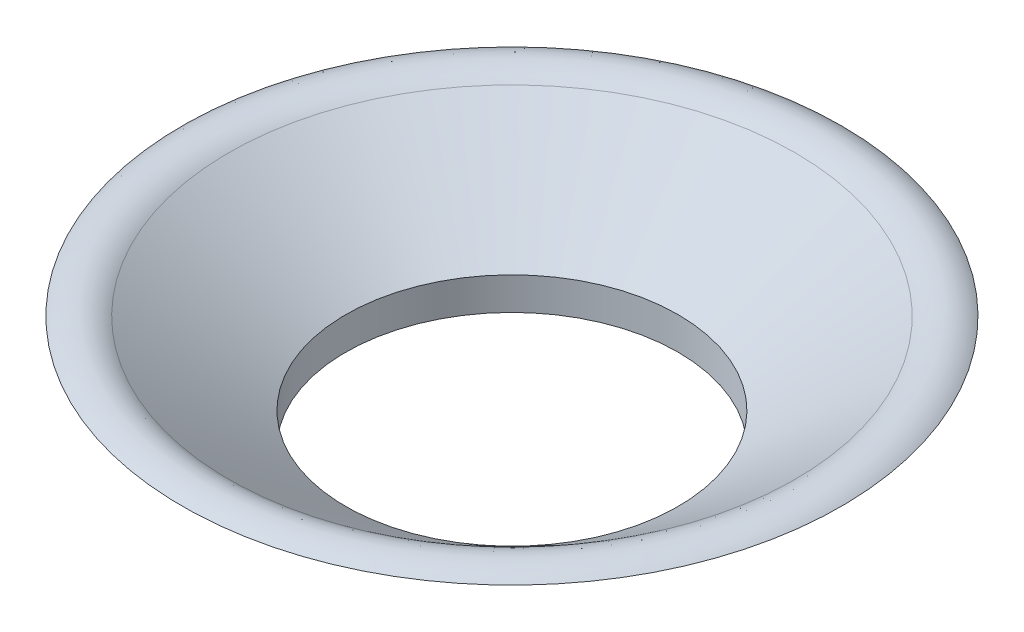
SolidWorks part; units mm, degrees
ref_plane "Front Plane" through (0, 0, 0) normal (0, 0, 1) x (1, 0, 0)
ref_plane "Top Plane" through (0, 0, 0) normal (0, 1, 0) x (1, 0, 0)
ref_plane "Right Plane" through (0, 0, 0) normal (1, 0, 0) x (0, 0, -1)
sketch "Sketch1" plane through (0, 0, 0) normal (0, 0, 1) x (1, 0, 0)
  line L0 (0, 0) -> (43.4688, 0) construction
  line L1 (50, 0) -> (99.1491, 34.4146)
  line L2 (50, 0) -> (50, 9.7999)
  line L3 (50, 9.7999) -> (85.1534, 34.4146)
  line L4 (85.1534, 34.4146) -> (99.1491, 34.4146) construction
  line L5 (0, 0) -> (0, 15.9722) construction
  arc A0 (85.1534, 34.4146) -> (99.1491, 34.4146) centre (92.1513, 24.4206) cw
  dimension "D1" = 35
  dimension "D2" = 60
  dimension "D3" = 50
revolve "Revolve1" add sketch "Sketch1" angle 360 about L5
